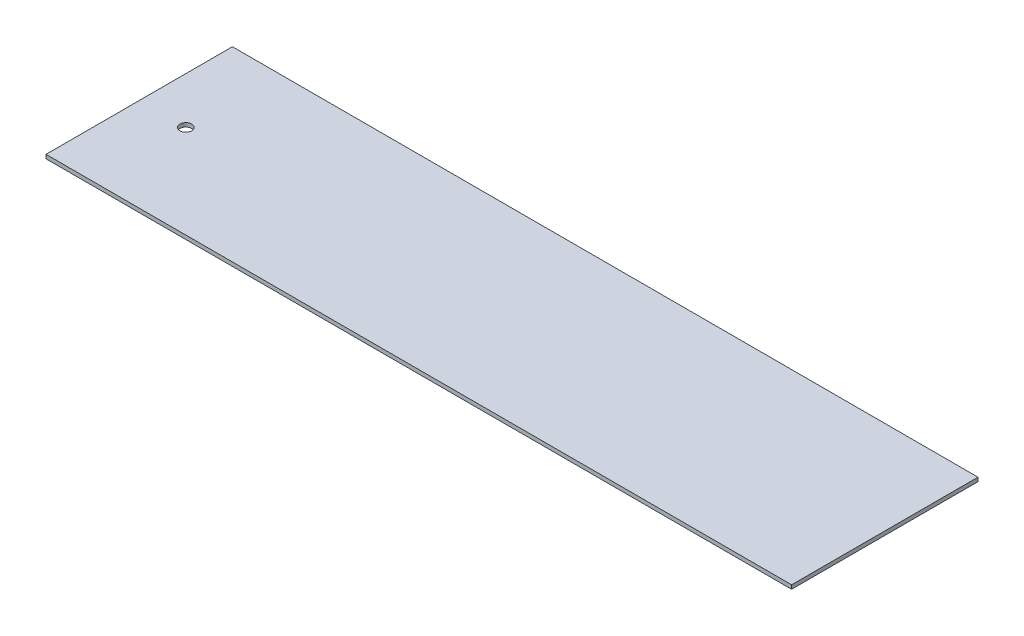
SolidWorks part; units mm, degrees
material "201 Annealed Stainless Steel (SS)"
ref_plane "Front Plane" through (0, 0, 0) normal (0, 0, 1) x (1, 0, 0)
ref_plane "Top Plane" through (0, 0, 0) normal (0, 1, 0) x (1, 0, 0)
ref_plane "Right Plane" through (0, 0, 0) normal (1, 0, 0) x (0, 0, -1)
sketch "Sketch1" plane through (0, 0, 0) normal (0, 1, 0) x (1, 0, 0)
  line L1 (0, 0) -> (304.8, 0)
  line L2 (0, 0) -> (0, 76.2)
  line L3 (0, 76.2) -> (304.8, 76.2)
  line L4 (304.8, 0) -> (304.8, 76.2)
  dimension "D1" = 304.8
  dimension "D2" = 76.2
extrude "Electrode Base" add sketch "Sketch1" along normal blind 1.5875
sketch "Sketch2" plane through (0, 1.5875, 0) normal (0, 1, 0) x (1, 0, 0)
  line L0 (0, 38.1) -> (304.8, 38.1) construction
  line L1 (0, 76.2) -> (0, 0) construction
  line L2 (304.8, 0) -> (304.8, 76.2) construction
  line L3 (152.4, 76.2) -> (152.4, 0) construction
  line L4 (304.8, 76.2) -> (0, 76.2) construction
  line L5 (0, 0) -> (304.8, 0) construction
  circle A1 centre (19.05, 38.1) radius 2.413
  dimension "D2" = 4.826
extrude "Cut-Extrude1" cut sketch "Sketch2" against normal through all
